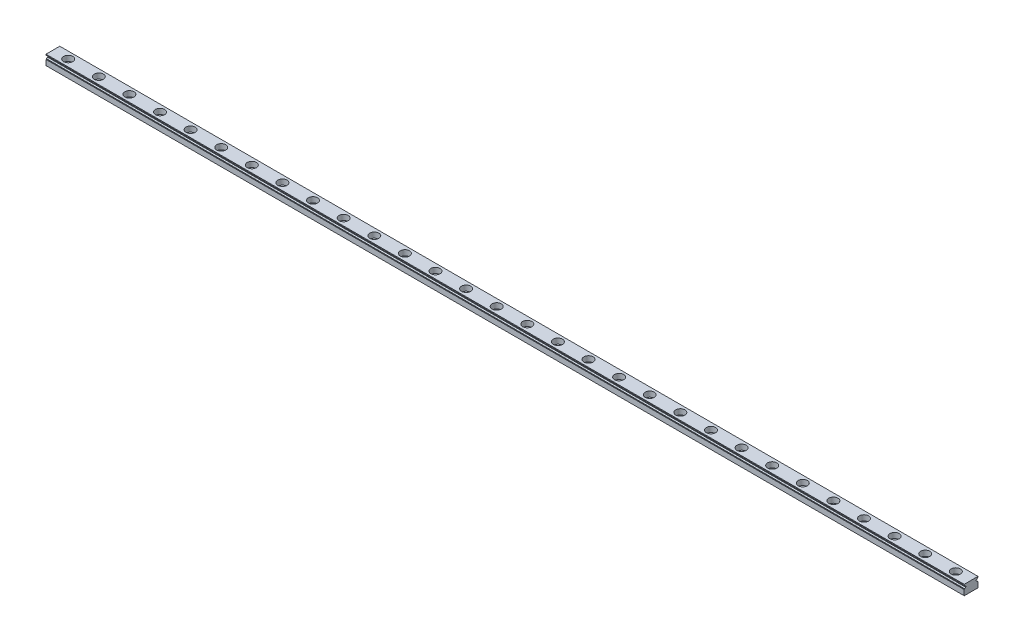
SolidWorks part; units mm, degrees
ref_plane "Plan de face" through (0, 0, 0) normal (0, 0, 1) x (1, 0, 0)
ref_plane "Plan de dessus" through (0, 0, 0) normal (0, 1, 0) x (1, 0, 0)
ref_plane "Plan de droite" through (0, 0, 0) normal (1, 0, 0) x (0, 0, -1)
other "L"
other "e"
sketch "Esquisse1" plane through (0, 0, 0) normal (1, 0, 0) x (0, 0, -1)
  line L0 (0, 0) -> (0, 10.8057) construction
  line L1 (-4.5, 0) -> (4.5, 0)
  line L2 (4.5, 0) -> (4.5, 3.5)
  line L3 (4.5, 3.5) -> (3.6, 4.4)
  line L4 (3.6, 4.4) -> (3.3, 4.4)
  line L5 (3.3, 4.4) -> (3.3, 5)
  line L6 (4.5, 5.9) -> (3.6, 5)
  line L7 (3.6, 5) -> (3.3, 5)
  line L8 (4.5, 5.9) -> (4.5, 6.5)
  line L9 (4.5, 6.5) -> (-4.5, 6.5)
  line L10 (3.3, 4.7) -> (8.4079, 4.7) construction
  line L11 (-4.5, 5.9) -> (-4.5, 6.5)
  line L12 (-4.5, 5.9) -> (-3.6, 5)
  line L13 (-3.6, 5) -> (-3.3, 5)
  line L14 (-3.3, 4.4) -> (-3.3, 5)
  line L15 (-3.6, 4.4) -> (-3.3, 4.4)
  line L16 (-4.5, 3.5) -> (-3.6, 4.4)
  line L17 (-4.5, 0) -> (-4.5, 3.5)
  point P18 (0, 6.5)
  dimension "D1" = 6.5
  dimension "D2" = 9
  dimension "D3" = 0.6
  dimension "D4" = 1.2
  dimension "D5" = 2.4
  dimension "D6" = 4.7
extrude "Boss.-Extru.1" add sketch "Esquisse1" along normal blind 600
sketch "Esquisse2" plane through (0, 0, 0) normal (1, 0, 0) x (0, 0, -1)
  line L0 (3.3, 5) -> (3.6, 5) construction
  line L1 (4.5, 5.9) -> (4.2, 5.9)
  line L2 (4.5, 5.9) -> (4.5, 3.5)
  line L3 (4.5, 3.5) -> (4.2, 3.5)
  line L4 (4.2, 5.9) -> (4.2, 3.5)
  line L5 (0, 0) -> (0, 7.1139) construction
  line L6 (-4.5, 5.9) -> (-4.2, 5.9)
  line L7 (-4.5, 5.9) -> (-4.5, 3.5)
  line L8 (-4.5, 3.5) -> (-4.2, 3.5)
  line L9 (-4.2, 5.9) -> (-4.2, 3.5)
extrude "Enlèv. mat.-Extru.1" cut sketch "Esquisse2" along normal through all
hole_wizard "Chambrage pour vis à tête hexagonale M31" positions "Esquisse3" profile "Esquisse4" counterbore size "M3" standard "ISO" end condition through all
sketch "Esquisse3" plane through (0, 6.5, 0) normal (0, 1, 0) x (1, 0, 0)
  line L0 (0, 4.5) -> (0, -4.5) construction
  point P0 (10, 0)
  point P6 (0, 0)
  dimension "D1" = 10
sketch "Esquisse4" plane through (10, 6.5, 0) normal (1, 0, 0) x (0, 0, 1)
  line L0 (0, 0) -> (0, 6.5)
  line L1 (0, 6.5) -> (1.75, 6.5)
  line L3 (1.75, 6.5) -> (1.75, 3.5)
  line L4 (1.75, 3.5) -> (3, 3.5)
  line L5 (3, 3.5) -> (3, 0)
  line L7 (3, 0) -> (0, 0)
  line L11 (0, -6.35) -> (0, 107.95) construction
  dimension "Diamètre du perçage jusqu'au prochain" = 3.5
  dimension "Profondeur du perçage jusqu'au prochain" = 6.5
  dimension "Diamètre du chambrage" = 6
  dimension "Profondeur du chambrage" = 3.5
pattern_linear "Répétition linéaire1" count 30 spacing 20 along (1, 0, 0) of "Chambrage pour vis à tête hexagonale M31"
ref_plane "SYM" through (300, 0, 0) normal (-1, 0, 0) x (0, 0, 1)
move or copy body "Corps-Déplacer/Copier1" [suppressed] bodies to move or copy 104
equation "\"D1@SYM\"=\"D1@Boss.-Extru.1\"/2"
